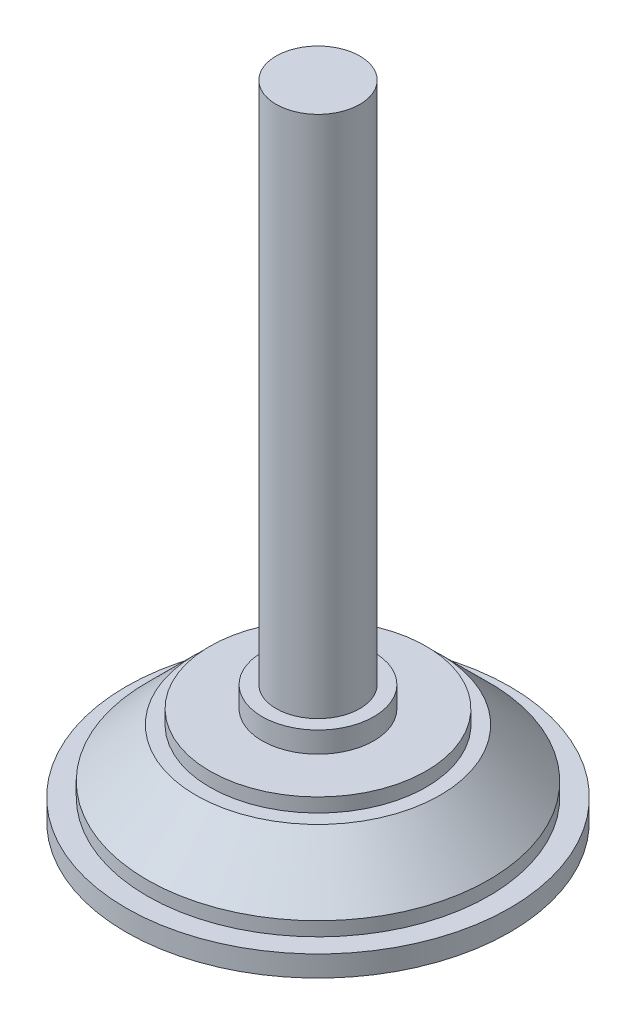
SolidWorks part; units mm, degrees
ref_plane "Plan de face" through (0, 0, 0) normal (0, 0, 1) x (1, 0, 0)
ref_plane "Plan de dessus" through (0, 0, 0) normal (0, 1, 0) x (1, 0, 0)
ref_plane "Plan de droite" through (0, 0, 0) normal (1, 0, 0) x (0, 0, -1)
sketch "Esquisse1" plane through (0, 0, 0) normal (0, 0, 1) x (1, 0, 0)
  line L0 (0, 0) -> (27.5, 0)
  line L1 (27.5, 0) -> (27.5, 3)
  line L2 (27.5, 3) -> (24.5, 3)
  line L3 (24.5, 3) -> (24.5, 5)
  line L4 (24.5, 5) -> (17.5, 12)
  line L5 (17.5, 12) -> (15.5, 12)
  line L6 (15.5, 12) -> (15.5, 14)
  line L7 (15.5, 14) -> (8, 14)
  line L8 (8, 14) -> (8, 17)
  line L9 (8, 17) -> (6, 17)
  line L10 (6, 17) -> (6, 92)
  line L11 (6, 92) -> (0, 92)
  line L12 (0, 0) -> (0, 92)
  line L13 (0, 92) -> (0, 0) construction
  point P14 (10.2649, 20.1393)
  point P15 (19.5555, 0.9203)
  point P16 (16.4526, 11.4029)
  point P17 (19.4716, 9.2225)
  point P18 (21.7358, 3.52)
  point P19 (14.7649, 14.7351)
  dimension "D1" = 55
  dimension "D2" = 75
  dimension "D3" = 3
  dimension "D4" = 3
  dimension "D5" = 2
  dimension "D6" = 135
  dimension "D7" = 2
  dimension "D8" = 3
  dimension "D9" = 16
  dimension "D10" = 12
  dimension "D11" = 2
  dimension "D12" = 12
revolve "Révolution1" add sketch "Esquisse1" angle 360 about L13
